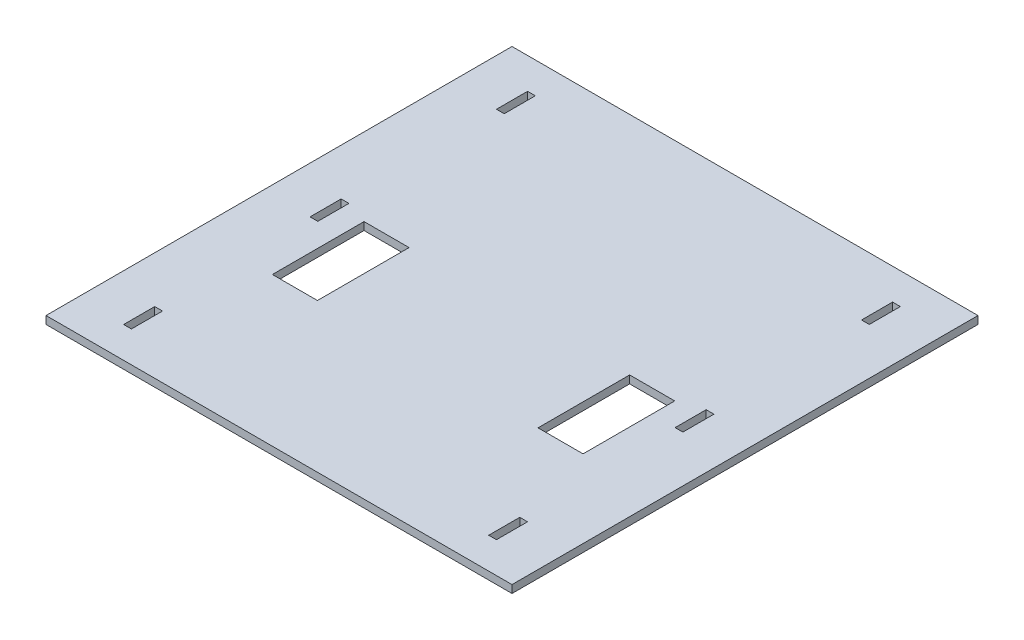
SolidWorks part; units mm, degrees
ref_plane "Front Plane" through (0, 0, 0) normal (0, 0, 1) x (1, 0, 0)
ref_plane "Top Plane" through (0, 0, 0) normal (0, 1, 0) x (1, 0, 0)
ref_plane "Right Plane" through (0, 0, 0) normal (1, 0, 0) x (0, 0, -1)
sketch "Sketch1" plane through (0, 0, 0) normal (0, 1, 0) x (1, 0, 0)
  line L1 (0, 0) -> (300, 0)
  line L2 (0, 0) -> (0, 300)
  line L3 (0, 300) -> (300, 300)
  line L4 (300, 0) -> (300, 300)
  dimension "D1" = 300
  dimension "D2" = 300
extrude "Boss-Extrude1" add sketch "Sketch1" along normal blind 5
sketch "Sketch2" plane through (0, 5, 0) normal (0, 1, 0) x (1, 0, 0)
  line L0 (300, 300) -> (0, 300) construction
  line L1 (250, 95.75) -> (221, 95.75)
  line L2 (250, 95.75) -> (250, 154.75)
  line L3 (250, 154.75) -> (221, 154.75)
  line L4 (221, 95.75) -> (221, 154.75)
  line L5 (79, 95.75) -> (50, 95.75)
  line L6 (79, 95.75) -> (79, 154.75)
  line L7 (79, 154.75) -> (50, 154.75)
  line L8 (50, 95.75) -> (50, 154.75)
  line L10 (300, 0) -> (300, 300) construction
  line L11 (0, 300) -> (0, 0) construction
  dimension "D1" = 29
  dimension "D2" = 29
  dimension "D3" = 59
  dimension "D4" = 59
  dimension "D5" = 145.25
  dimension "D6" = 145.25
  dimension "D7" = 50
  dimension "D8" = 50
extrude "Cut-Extrude1" cut sketch "Sketch2" against normal blind 5
sketch "Sketch3" plane through (0, 5, 0) normal (0, 1, 0) x (1, 0, 0)
  line L0 (0, 0) -> (300, 0) construction
  line L1 (270, 20) -> (265, 20)
  line L2 (270, 20) -> (270, 40)
  line L3 (270, 40) -> (265, 40)
  line L4 (265, 20) -> (265, 40)
  line L5 (270, 140) -> (265, 140)
  line L6 (270, 140) -> (270, 160)
  line L7 (270, 160) -> (265, 160)
  line L8 (265, 140) -> (265, 160)
  line L9 (270, 260) -> (265, 260)
  line L10 (270, 260) -> (270, 280)
  line L11 (270, 280) -> (265, 280)
  line L12 (265, 260) -> (265, 280)
  line L13 (35, 20) -> (30, 20)
  line L14 (35, 20) -> (35, 40)
  line L15 (35, 40) -> (30, 40)
  line L16 (30, 20) -> (30, 40)
  line L17 (35, 140) -> (30, 140)
  line L18 (35, 140) -> (35, 160)
  line L19 (35, 160) -> (30, 160)
  line L20 (30, 140) -> (30, 160)
  line L21 (35, 260) -> (30, 260)
  line L22 (35, 260) -> (35, 280)
  line L23 (35, 280) -> (30, 280)
  line L24 (30, 260) -> (30, 280)
  line L25 (300, 0) -> (300, 300) construction
  line L26 (300, 300) -> (0, 300) construction
  line L27 (0, 300) -> (0, 0) construction
  dimension "D1" = 5
  dimension "D2" = 20
  dimension "D3" = 5
  dimension "D4" = 20
  dimension "D5" = 20
  dimension "D6" = 5
  dimension "D7" = 20
  dimension "D8" = 5
  dimension "D9" = 5
  dimension "D10" = 20
  dimension "D11" = 5
  dimension "D12" = 20
  dimension "D13" = 20
  dimension "D14" = 30
  dimension "D15" = 140
  dimension "D16" = 30
  dimension "D17" = 20
  dimension "D18" = 30
  dimension "D19" = 30
  dimension "D20" = 20
  dimension "D21" = 30
  dimension "D22" = 140
  dimension "D23" = 20
  dimension "D24" = 30
extrude "Cut-Extrude2" cut sketch "Sketch3" against normal blind 5
